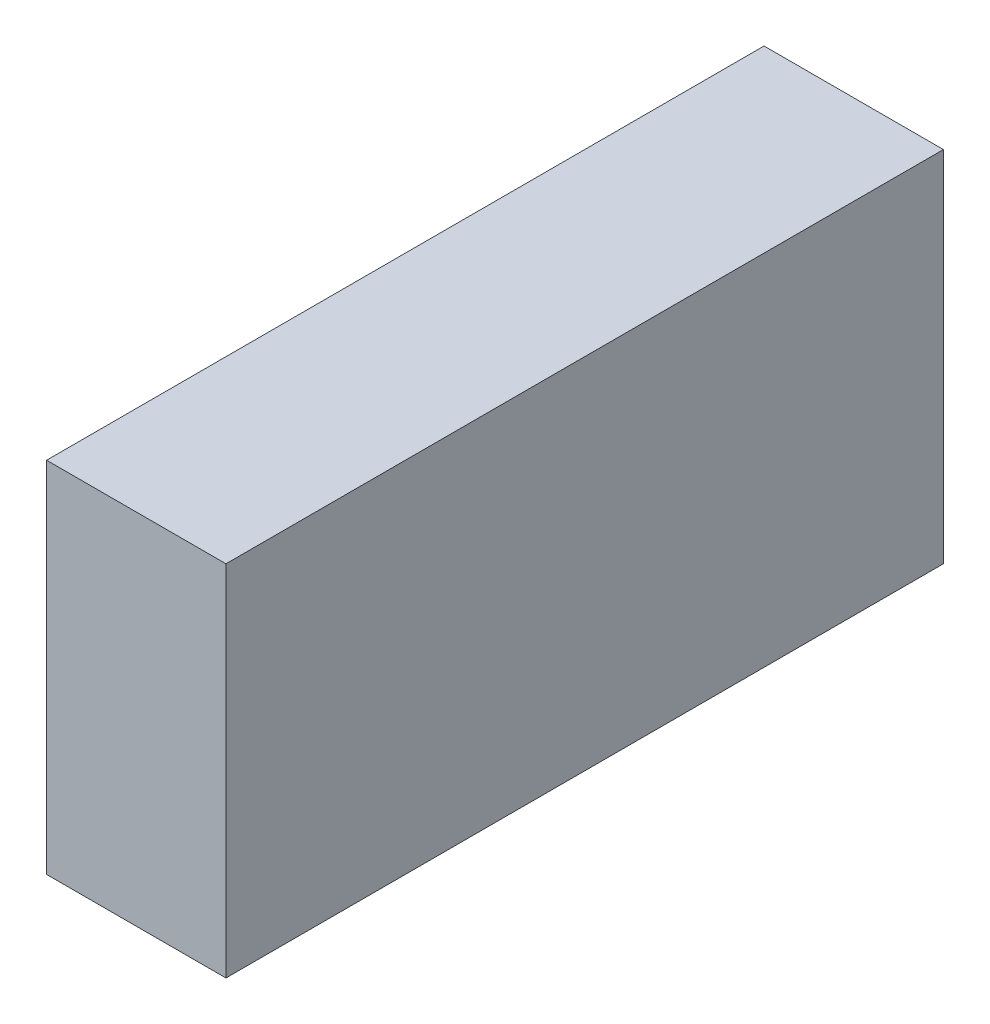
SolidWorks part; units mm, degrees
ref_plane "Front Plane" through (0, 0, 0) normal (0, 0, 1) x (1, 0, 0)
ref_plane "Top Plane" through (0, 0, 0) normal (0, 1, 0) x (1, 0, 0)
ref_plane "Right Plane" through (0, 0, 0) normal (1, 0, 0) x (0, 0, -1)
sketch "Sketch1" plane through (0, 0, 0) normal (1, 0, 0) x (0, 0, -1)
  line L0 (0, 0) -> (40, 0)
  line L1 (40, 0) -> (40, 20)
  line L2 (40, 20) -> (0, 20)
  line L3 (0, 20) -> (0, 0)
extrude "Boss-Extrude1" add sketch "Sketch1" along normal blind 10
